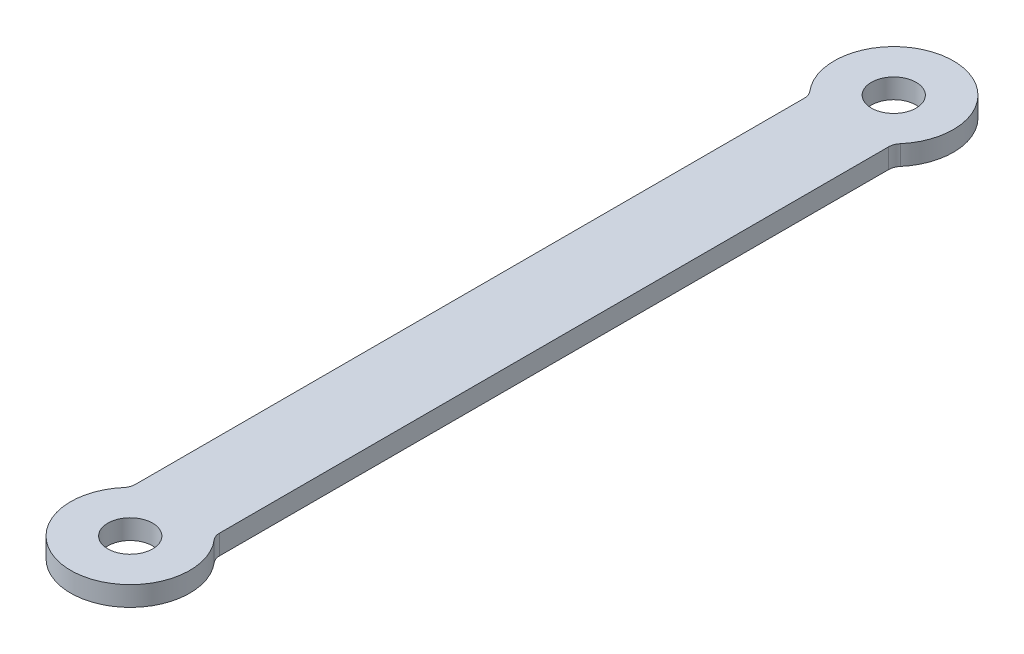
SolidWorks part; units mm, degrees
ref_plane "Front Plane" through (0, 0, 0) normal (0, 0, 1) x (1, 0, 0)
ref_plane "Top Plane" through (0, 0, 0) normal (0, 1, 0) x (1, 0, 0)
ref_plane "Right Plane" through (0, 0, 0) normal (1, 0, 0) x (0, 0, -1)
sketch "Sketch2" plane through (0, 0, 0) normal (0, 1, 0) x (1, 0, 0)
  line L0 (0, 29) -> (0, -29) construction
  line L1 (4.525, 29) -> (0, 29) construction
  line L2 (0, 29) -> (3.1997, 25.8003) construction
  line L3 (3.1997, 25.8003) -> (3.1997, -25.8003)
  line L4 (-3.1997, 25.8003) -> (-3.1997, -25.8003)
  circle A0 centre (0, 29) radius 4.525
  circle A1 centre (0, -29) radius 4.525
  point P4 (0, 0)
  dimension "D2" = 9.05
  dimension "D1" = 58
  dimension "D3" = 45
extrude "Boss-Extrude1" add sketch "Sketch2" along normal blind 1.5 contours A1 | A1 L3 A0 L4 | A0
sketch "Sketch3" plane through (0, 1.5, 0) normal (0, 1, 0) x (1, 0, 0)
  line L0 (0, -29) -> (0, 29) construction
  point P4 (0, 0)
  dimension "D1" = 58
hole_wizard "M3 Clearance Hole1" positions "Sketch4" profile "Sketch5" hole size "M3" standard "BSI" end condition through all
sketch "Sketch4" plane through (0, 1.5, 0) normal (0, 1, 0) x (1, 0, 0)
  point P0 (0, 29)
  point P3 (0, -29)
sketch "Sketch5" plane through (0, 1.5, -29) normal (1, 0, 0) x (0, 0, 1)
  line L0 (0, 0) -> (0, 1.5)
  line L1 (0, 1.5) -> (1.7, 1.5)
  line L2 (1.7, 1.5) -> (1.7, 0)
  line L5 (1.7, 0) -> (0, 0)
  line L11 (0, -6.35) -> (0, 107.95) construction
  dimension "Thru Hole Dia." = 3.4
  dimension "Thru Hole Depth" = 1.5
fillet "Fillet1" radius 1 4 edges at (-3.1997, 0.75, -25.8003) (-3.1997, 0.75, 25.8003) (3.1997, 0.75, 25.8003) (3.1997, 0.75, -25.8003)
